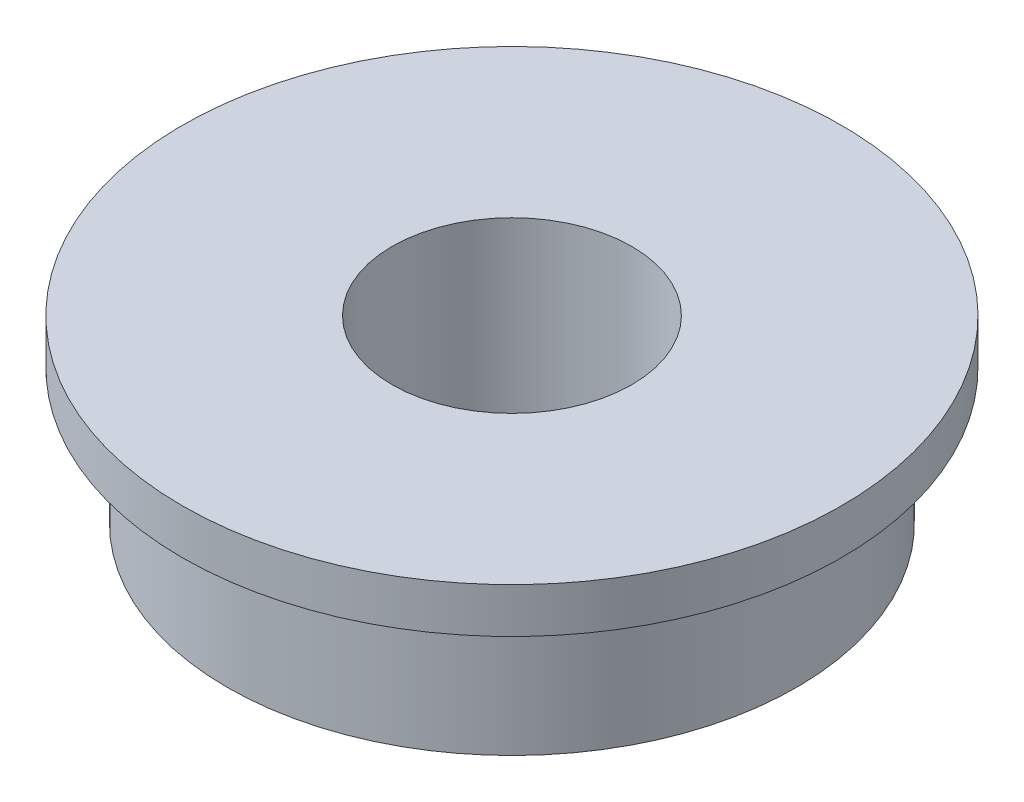
SolidWorks part; units mm, degrees
ref_plane "前视基准面" through (0, 0, 0) normal (0, 0, 1) x (1, 0, 0)
ref_plane "上视基准面" through (0, 0, 0) normal (0, 1, 0) x (1, 0, 0)
ref_plane "右视基准面" through (0, 0, 0) normal (1, 0, 0) x (0, 0, -1)
sketch "草图1" plane through (0, 0, 0) normal (0, 1, 0) x (1, 0, 0)
  circle A0 centre (0, 0) radius 9.5
  dimension "D1" = 19
extrude "凸台-拉伸1" add sketch "草图1" along normal blind 4.5
sketch "草图2" plane through (0, 4.5, 0) normal (0, 1, 0) x (1, 0, 0)
  circle A0 centre (0, 0) radius 11
  dimension "D1" = 22
extrude "凸台-拉伸2" add sketch "草图2" along normal blind 1.5
sketch "草图3" plane through (0, 6, 0) normal (0, 1, 0) x (1, 0, 0)
  circle A0 centre (0, 0) radius 4
  dimension "D1" = 8
extrude "切除-拉伸1" cut sketch "草图3" against normal through all
